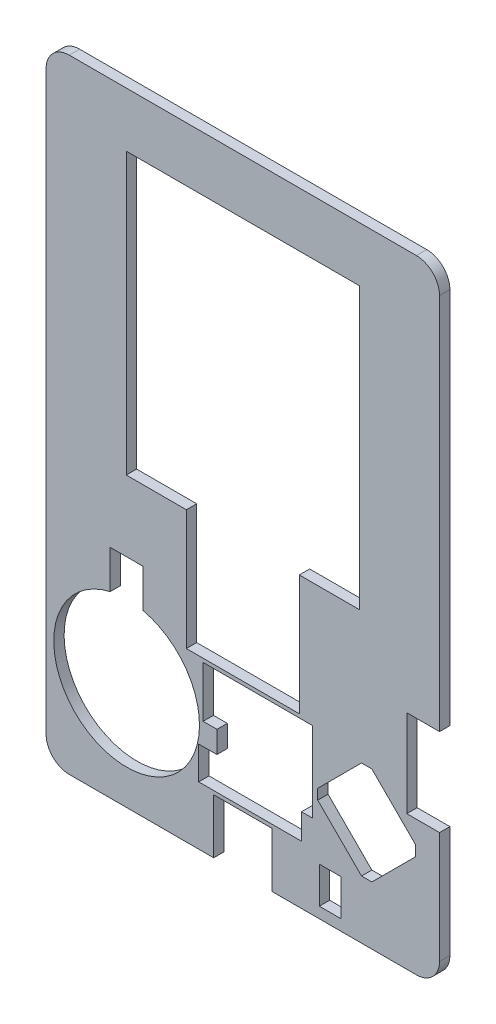
SolidWorks part; units mm, degrees
ref_plane "前视基准面" through (0, 0, 0) normal (0, 0, 1) x (1, 0, 0)
ref_plane "上视基准面" through (0, 0, 0) normal (0, 1, 0) x (1, 0, 0)
ref_plane "右视基准面" through (0, 0, 0) normal (1, 0, 0) x (0, 0, -1)
sketch "草图1" plane through (0, 0, 0) normal (0, 0, 1) x (1, 0, 0)
  line L1 (-23.82, -42.75) -> (23.82, -42.75)
  line L2 (-27, -39.57) -> (-27, 39.57)
  line L3 (-23.82, 42.75) -> (23.82, 42.75)
  line L4 (27, -39.57) -> (27, 39.57)
  line L5 (-27, -42.75) -> (27, 42.75) construction
  line L6 (-27, 42.75) -> (27, -42.75) construction
  arc A0 (23.82, -42.75) -> (27, -39.57) centre (23.82, -39.57) ccw
  arc A1 (-23.82, -42.75) -> (-27, -39.57) centre (-23.82, -39.57) cw
  arc A2 (-27, 39.57) -> (-23.82, 42.75) centre (-23.82, 39.57) cw
  arc A3 (23.82, 42.75) -> (27, 39.57) centre (23.82, 39.57) cw
  point P0 (0, 0)
  dimension "D3" = 3.18
  dimension "D1" = 54
  dimension "D2" = 85.5
extrude "凸台-拉伸1" add sketch "草图1" along normal blind 1.42
sketch "草图2" plane through (0, 0, 1.42) normal (0, 0, 1) x (1, 0, 0)
  line L0 (23.82, 42.75) -> (-23.82, 42.75) construction
  line L1 (-16, 35.25) -> (16, 35.25)
  line L2 (-16, 35.25) -> (-16, -3.25)
  line L3 (-16, -3.25) -> (16, -3.25)
  line L4 (16, 35.25) -> (16, -3.25)
  line L5 (-16, 35.25) -> (16, -3.25) construction
  line L6 (-16, -3.25) -> (16, 35.25) construction
  line L8 (7.75, -19.75) -> (-7.75, -19.75)
  line L9 (7.75, -19.75) -> (7.75, -3.25)
  line L10 (7.75, -3.25) -> (-7.75, -3.25)
  line L11 (-7.75, -19.75) -> (-7.75, -3.25)
  line L12 (7.75, -19.75) -> (-7.75, -3.25) construction
  line L13 (7.75, -3.25) -> (-7.75, -19.75) construction
  point P0 (0, 16)
  point P5 (0, -11.5)
  point P13 (0, 0)
  dimension "D1" = 32
  dimension "D2" = 38.5
  dimension "D3" = 7.5
  dimension "D4" = 15.5
  dimension "D5" = 16.5
extrude "切除-拉伸1" cut sketch "草图2" against normal up to next contours L4 L1 L2 L3 | L11 L8 L9 L3
sketch "草图3" plane through (0, 0, 1.42) normal (0, 0, 1) x (1, 0, 0)
  line L0 (-27, 39.57) -> (-27, -39.57) construction
  line L1 (-23.82, -42.75) -> (23.82, -42.75) construction
  line L4 (-18.2, -18.2064) -> (-18.2, -12.95)
  line L5 (-18.2, -12.95) -> (-13.7, -12.95)
  line L6 (-13.7, -18.2064) -> (-13.7, -12.95)
  circle A0 centre (-15.95, -27.95) radius 10
  point P6 (-15.95, -16.2368)
  point P11 (-13.7, -18.2064)
  point P12 (-18.2, -18.2064)
  dimension "D1" = 20
  dimension "D2" = 11.05
  dimension "D3" = 14.8
  dimension "D4" = 4.5
  dimension "D5" = 15
extrude "切除-拉伸2" cut sketch "草图3" against normal up to next contours A0 | A0 L6 L5 L4
sketch "草图4" plane through (0, 0, 1.42) normal (0, 0, 1) x (1, 0, 0)
  line L0 (-5.45, -20.25) -> (9.55, -20.25)
  line L1 (9.55, -20.25) -> (9.55, -31.25)
  line L2 (9.55, -31.25) -> (8.05, -31.25)
  line L3 (8.05, -31.25) -> (8.05, -34.75)
  line L4 (8.05, -34.75) -> (-6.05, -34.75)
  line L5 (-6.05, -34.75) -> (-6.05, -30.25)
  line L6 (-6.05, -30.25) -> (-3.55, -30.25)
  line L7 (-3.55, -30.25) -> (-3.55, -27.25)
  line L8 (-3.55, -27.25) -> (-5.45, -27.25)
  line L9 (-5.45, -27.25) -> (-5.45, -20.25)
  line L10 (7.75, -19.75) -> (-7.75, -19.75) construction
  arc A0 (-18.2, -18.2064) -> (-13.7, -18.2064) centre (-15.95, -27.95) ccw construction
  dimension "D1" = 0.5
  dimension "D2" = 10.5
  dimension "D3" = 15
  dimension "D4" = 11
  dimension "D5" = 1.5
  dimension "D6" = 3.5
  dimension "D7" = 7
  dimension "D8" = 3
  dimension "D9" = 0.6
  dimension "D10" = 1.9
extrude "切除-拉伸3" cut sketch "草图4" against normal up to next
sketch "草图5" plane through (0, 0, 1.42) normal (0, 0, 1) x (1, 0, 0)
  line L0 (-23.82, -42.75) -> (23.82, -42.75) construction
  line L1 (-4, -42.75) -> (4, -42.75)
  line L2 (-4, -42.75) -> (-4, -35.25)
  line L3 (-4, -35.25) -> (4, -35.25)
  line L4 (4, -42.75) -> (4, -35.25)
  line L5 (-4, -42.75) -> (4, -35.25) construction
  line L6 (-4, -35.25) -> (4, -42.75) construction
  point P0 (0, -39)
  point P7 (0, 0)
  dimension "D1" = 8
  dimension "D2" = 7.5
extrude "切除-拉伸4" cut sketch "草图5" against normal up to next
sketch "草图6" plane through (0, 0, 1.42) normal (0, 0, 1) x (1, 0, 0)
  line L0 (4, -42.75) -> (23.82, -42.75) construction
  line L1 (10.5, -41.25) -> (13.5, -41.25)
  line L2 (10.5, -41.25) -> (10.5, -36.25)
  line L3 (10.5, -36.25) -> (13.5, -36.25)
  line L4 (13.5, -41.25) -> (13.5, -36.25)
  line L5 (10.5, -41.25) -> (13.5, -36.25) construction
  line L6 (10.5, -36.25) -> (13.5, -41.25) construction
  line L7 (27, -39.57) -> (27, 39.57) construction
  line L8 (17.7071, -34.7675) -> (23.7175, -28.7571)
  line L9 (16.2929, -34.7675) -> (10.2825, -28.7571)
  line L10 (23.7175, -27.3429) -> (17.7071, -21.3325)
  line L11 (10.2825, -27.3429) -> (16.2929, -21.3325)
  line L12 (17, -35.4746) -> (17, -20.6254) construction
  line L13 (24.4246, -28.05) -> (9.5754, -28.05) construction
  line L14 (10.2825, -28.7571) -> (10.2825, -27.3429)
  line L15 (17.7071, -21.3325) -> (16.2929, -21.3325)
  line L16 (23.7175, -28.7571) -> (23.7175, -27.3429)
  line L17 (17.7071, -34.7675) -> (16.2929, -34.7675)
  point P0 (12, -38.75)
  point P10 (17, -28.05)
  dimension "D1" = 3
  dimension "D2" = 5
  dimension "D3" = 1.5
  dimension "D4" = 13.5
  dimension "D5" = 10.5
  dimension "D6" = 10.5
  dimension "D7" = 14.7
  dimension "D8" = 10
extrude "切除-拉伸5" cut sketch "草图6" against normal up to next
sketch "草图7" plane through (0, 0, 1.42) normal (0, 0, 1) x (1, 0, 0)
  line L0 (27, -39.57) -> (27, 39.57) construction
  line L1 (27, -24.25) -> (22.5, -24.25)
  line L2 (27, -24.25) -> (27, -12.25)
  line L3 (27, -12.25) -> (22.5, -12.25)
  line L4 (22.5, -24.25) -> (22.5, -12.25)
  line L5 (27, -24.25) -> (22.5, -12.25) construction
  line L6 (27, -12.25) -> (22.5, -24.25) construction
  line L7 (4, -42.75) -> (23.82, -42.75) construction
  point P0 (24.75, -18.25)
  dimension "D1" = 12
  dimension "D2" = 4.5
  dimension "D3" = 18.5
extrude "切除-拉伸6" cut sketch "草图7" against normal up to next
